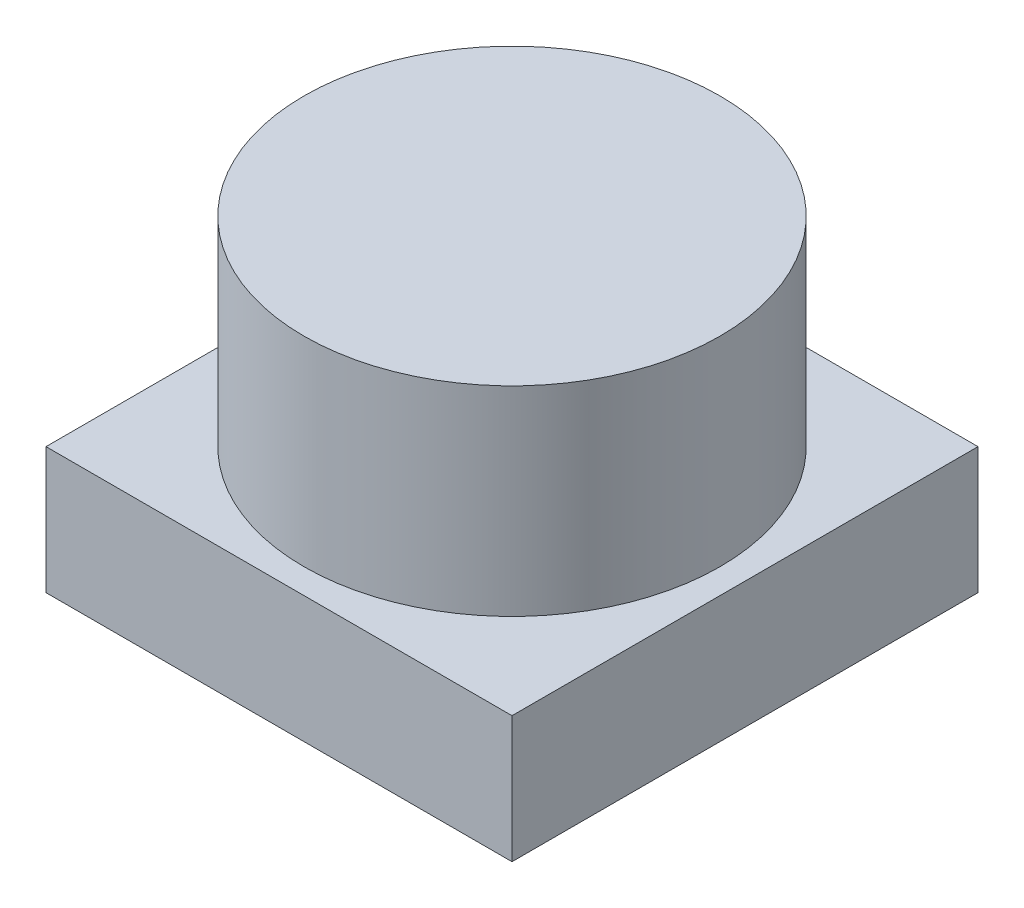
SolidWorks part; units mm, degrees
ref_plane "Front Plane" through (0, 0, 0) normal (0, 0, 1) x (1, 0, 0)
ref_plane "Top Plane" through (0, 0, 0) normal (0, 1, 0) x (1, 0, 0)
ref_plane "Right Plane" through (0, 0, 0) normal (1, 0, 0) x (0, 0, -1)
sketch "Sketch1" plane through (0, 0, 0) normal (0, 1, 0) x (1, 0, 0)
  line L1 (3.5, 3.5) -> (-3.5, 3.5)
  line L2 (3.5, 3.5) -> (3.5, -3.5)
  line L3 (3.5, -3.5) -> (-3.5, -3.5)
  line L4 (-3.5, 3.5) -> (-3.5, -3.5)
  line L5 (3.5, 3.5) -> (-3.5, -3.5) construction
  line L6 (3.5, -3.5) -> (-3.5, 3.5) construction
  point P0 (0, 0)
  dimension "D1" = 7
extrude "Boss-Extrude1" add sketch "Sketch1" along normal blind 1.9
sketch "Sketch2" plane through (0, 1.9, 0) normal (0, 1, 0) x (1, 0, 0)
  circle A0 centre (0, 0) radius 3.125
  dimension "D1" = 6.25
extrude "Boss-Extrude2" add sketch "Sketch2" along normal blind 3
